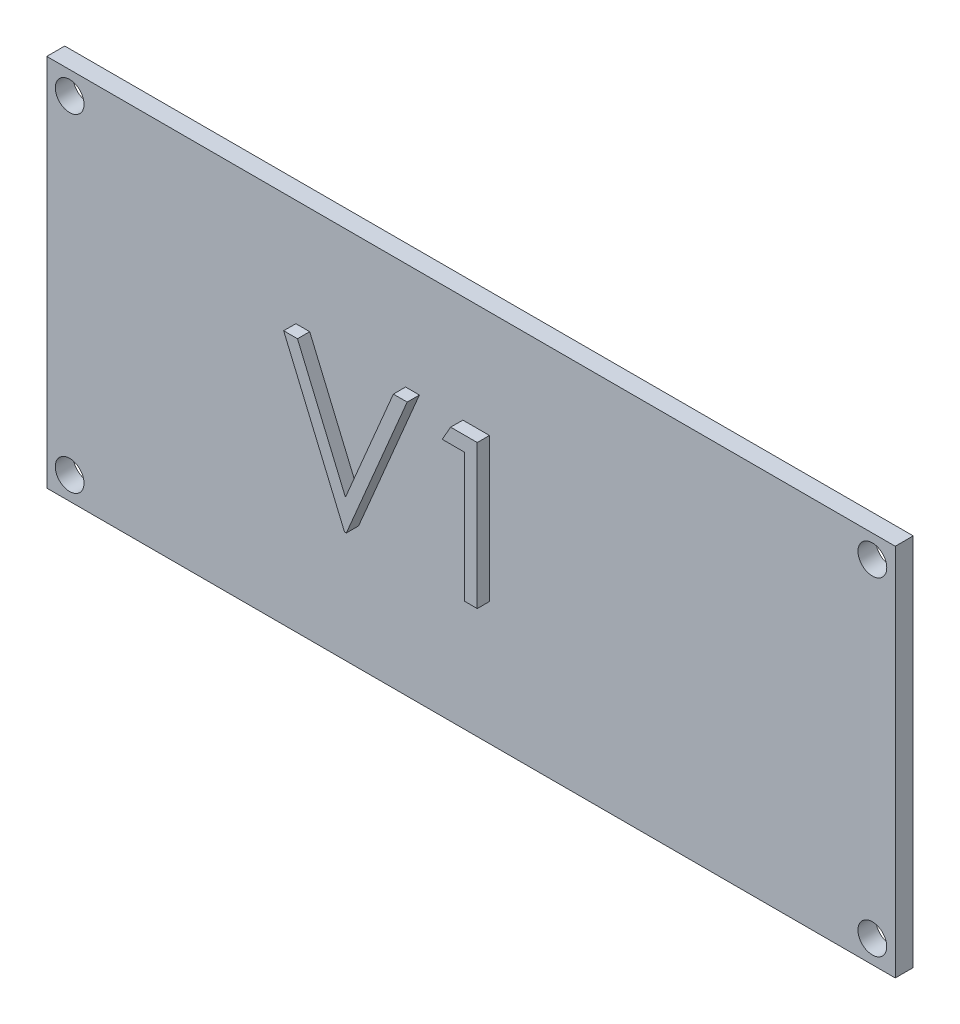
SolidWorks part; units mm, degrees
ref_plane "Front Plane" through (0, 0, 0) normal (0, 0, 1) x (1, 0, 0)
ref_plane "Top Plane" through (0, 0, 0) normal (0, 1, 0) x (1, 0, 0)
ref_plane "Right Plane" through (0, 0, 0) normal (1, 0, 0) x (0, 0, -1)
sketch "Sketch1" plane through (0, 0, 0) normal (0, 0, 1) x (1, 0, 0)
  line L0 (-19.8209, -132.0415) -> (-16.6389, -128.8595)
  line L1 (-19.8209, -80.0415) -> (98.1791, -80.0415)
  line L2 (-19.8209, -80.0415) -> (-19.8209, -132.0415)
  line L3 (-19.8209, -132.0415) -> (98.1791, -132.0415)
  line L4 (98.1791, -80.0415) -> (98.1791, -132.0415)
  line L5 (39.1791, -82.5415) -> (39.1791, -129.5415)
  line L8 (98.1791, -132.0415) -> (94.9971, -128.8595)
  line L9 (-17.3209, -106.0415) -> (98.1791, -106.0415)
  line L11 (98.1791, -80.0415) -> (94.9971, -83.2235)
  line L12 (-19.8209, -80.0415) -> (-16.6389, -83.2235)
  circle A0 centre (-16.6389, -128.8595) radius 2
  circle A1 centre (94.9971, -128.8595) radius 2
  circle A2 centre (94.9971, -83.2235) radius 2
  circle A3 centre (-16.6389, -83.2235) radius 2
extrude "Boss-Extrude1" add sketch "Sketch1" along normal blind 2.5
sketch "Sketch2" plane through (0, 0, 2.5) normal (0, 0, 1) x (1, 0, 0)
  text T0 "V1" font "Century Gothic" height 20
extrude "Boss-Extrude2" add sketch "Sketch2" along normal blind 1.7
